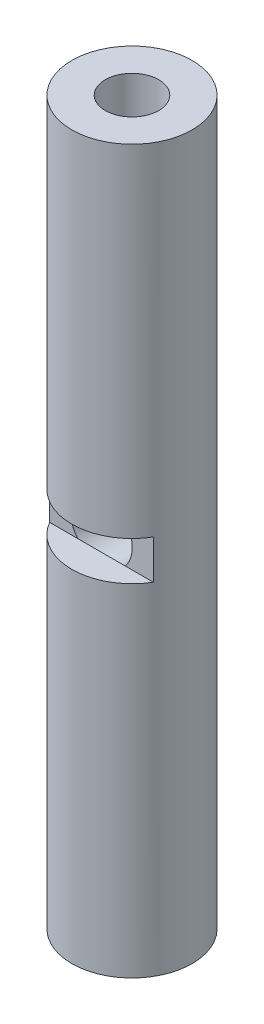
SolidWorks part; units mm, degrees
ref_plane "Front Plane" through (0, 0, 0) normal (0, 0, 1) x (1, 0, 0)
ref_plane "Top Plane" through (0, 0, 0) normal (0, 1, 0) x (1, 0, 0)
ref_plane "Right Plane" through (0, 0, 0) normal (1, 0, 0) x (0, 0, -1)
sketch "Sketch1" plane through (0, 0, 0) normal (0, 1, 0) x (1, 0, 0)
  circle A0 centre (0, 0) radius 2
  dimension "D1" = 4
extrude "Boss-Extrude1" add sketch "Sketch1" along normal mid plane 24
ref_plane "Plane1" through (0, 0, 1.016) normal (0, 0, 1) x (1, 0, 0)
sketch "Sketch2" plane through (0, 0, 1.016) normal (0, 0, 1) x (1, 0, 0)
  circle A0 centre (0, 0) radius 1.025
  dimension "D1" = 2.05
extrude "Cut-Extrude1" cut sketch "Sketch2" against normal blind 15.24 contours A0
sketch "Sketch3" plane through (0, 0, 1.016) normal (0, 0, -1) x (-1, 0, 0)
  line L0 (2, -12) -> (2, 12) construction
  line L1 (-2, 0.65) -> (2, 0.65)
  line L2 (-2, 0.65) -> (-2, -0.65)
  line L3 (-2, -0.65) -> (2, -0.65)
  line L4 (2, 0.65) -> (2, -0.65)
  line L5 (-2, 0.65) -> (2, -0.65) construction
  line L6 (-2, -0.65) -> (2, 0.65) construction
  dimension "D1" = 1.3
extrude "Cut-Extrude2" cut sketch "Sketch3" against normal blind 15.24
hole_wizard "#2-56 Tapped Hole1" positions "Sketch4" profile "Sketch5" tap size "#2-56" standard "ANSI Inch"
sketch "Sketch4" plane through (0, 12, 0) normal (0, 1, 0) x (1, 0, 0)
  point P0 (0, 0)
sketch "Sketch5" plane through (0, 12, 0) normal (1, 0, 0) x (0, 0, 1)
  line L0 (0, 0) -> (0, 9.5181)
  line L1 (0, 9.5181) -> (0.889, 8.984)
  line L2 (0.889, 8.984) -> (0.889, 0)
  line L5 (0.889, 0) -> (0, 0)
  line L10 (0, 9.5181) -> (-0.889, 8.984) construction
  line L11 (0, -6.35) -> (0, 107.95) construction
  dimension "Tap Drill Dia." = 1.778
  dimension "Tap Drill Depth" = 8.984
  dimension "Drill Angle" = 118
cosmetic thread "Hole Thread1" parameters "D1"=7.62, "D2"=2.1844
hole_wizard "#2-56 Tapped Hole2" positions "Sketch6" profile "Sketch7" tap size "#2-56" standard "ANSI Inch"
sketch "Sketch6" plane through (0, -12, 0) normal (0, -1, 0) x (-1, 0, 0)
  point P0 (0, 0)
sketch "Sketch7" plane through (0, -12, 0) normal (1, 0, 0) x (0, 0, -1)
  line L0 (0, 0) -> (0, 9.4242)
  line L1 (0, 9.4242) -> (0.889, 8.89)
  line L2 (0.889, 8.89) -> (0.889, 0)
  line L5 (0.889, 0) -> (0, 0)
  line L10 (0, 9.4242) -> (-0.889, 8.89) construction
  line L11 (0, -6.35) -> (0, 107.95) construction
  dimension "Tap Drill Dia." = 1.778
  dimension "Tap Drill Depth" = 8.89
  dimension "Drill Angle" = 118
cosmetic thread "Hole Thread2" parameters "D1"=7.62, "D2"=2.1844
